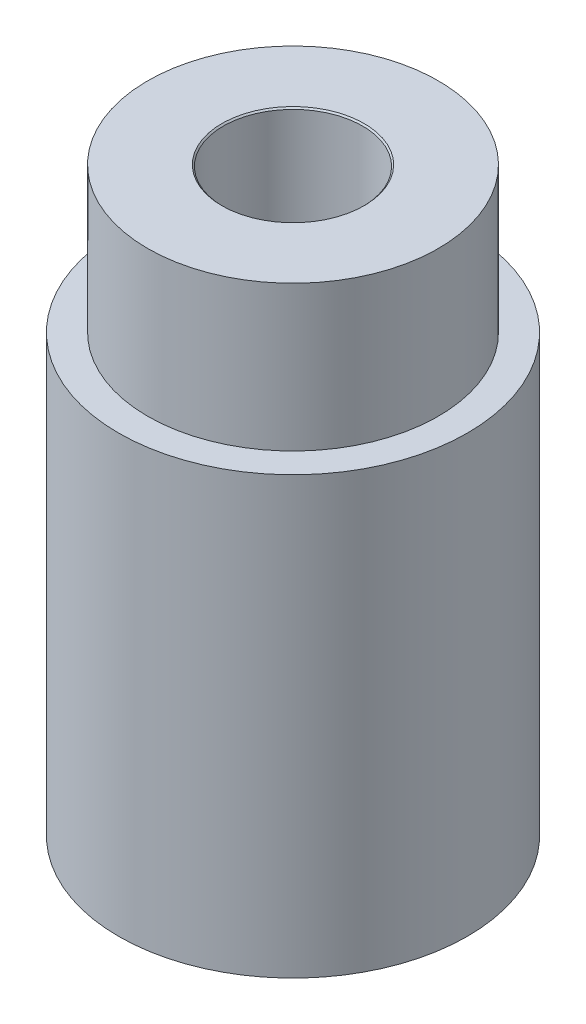
SolidWorks part; units mm, degrees
ref_plane "Front Plane" through (0, 0, 0) normal (0, 0, 1) x (1, 0, 0)
ref_plane "Top Plane" through (0, 0, 0) normal (0, 1, 0) x (1, 0, 0)
ref_plane "Right Plane" through (0, 0, 0) normal (1, 0, 0) x (0, 0, -1)
sketch "Sketch1" plane through (0, 0, 0) normal (0, 1, 0) x (1, 0, 0)
  circle A0 centre (0, 0) radius 3
  dimension "D1" = 6
extrude "Boss-Extrude1" add sketch "Sketch1" along normal blind 7.5
sketch "Sketch2" plane through (0, 7.5, 0) normal (0, 1, 0) x (1, 0, 0)
  circle A0 centre (0, 0) radius 2.5
  dimension "D1" = 5
extrude "Boss-Extrude2" add sketch "Sketch2" along normal blind 2.5
hole_wizard "M2 Clearance Hole1" positions "Sketch5" profile "Sketch4" hole size "M2" standard "ANSI Metric" end condition through all
sketch "Sketch5" plane through (0, 10, 0) normal (0, 1, 0) x (1, 0, 0)
  point P0 (0, 0)
sketch "Sketch4" plane through (0, 10, 0) normal (1, 0, 0) x (0, 0, 1)
  line L0 (0, 0) -> (0, 10)
  line L1 (0, 10) -> (1.2, 10)
  line L2 (1.2, 10) -> (1.2, 0.025)
  line L3 (1.2, 0.025) -> (1.225, 0)
  line L5 (1.225, 0) -> (0, 0)
  line L6 (-1.2, 0.025) -> (-1.225, 0) construction
  line L11 (0, -6.35) -> (0, 107.95) construction
  dimension "Thru Hole Dia." = 2.4
  dimension "Thru Hole Depth" = 10
  dimension "Near C'Sink Dia." = 2.45
  dimension "Near C'Sink Angle" = 90
